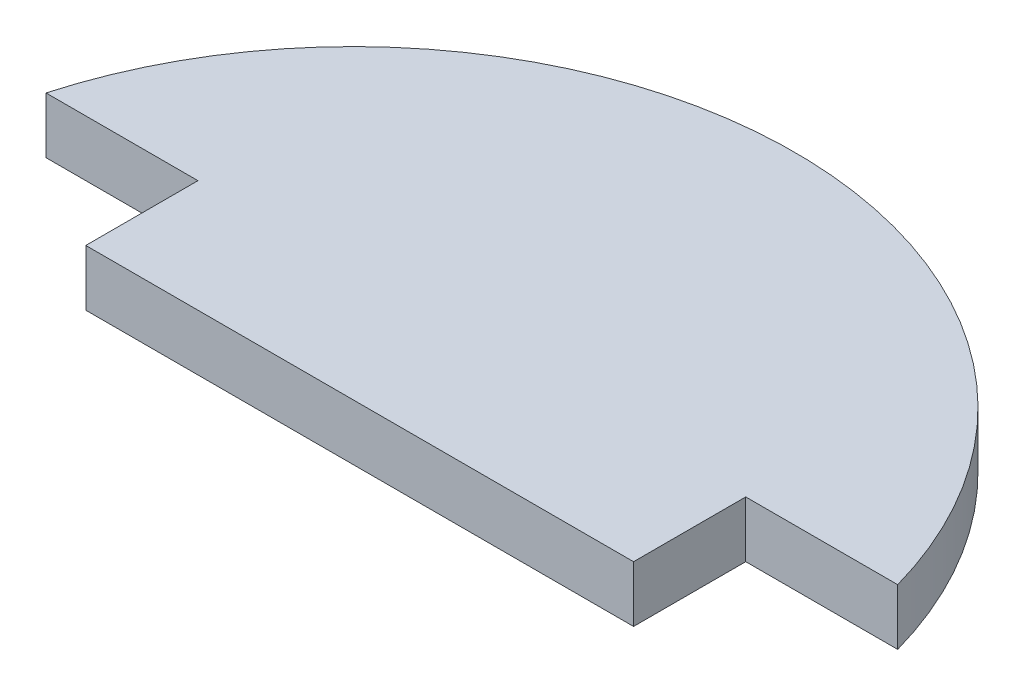
SolidWorks part; units mm, degrees
ref_plane "Front Plane" through (0, 0, 0) normal (0, 0, 1) x (1, 0, 0)
ref_plane "Top Plane" through (0, 0, 0) normal (0, 1, 0) x (1, 0, 0)
ref_plane "Right Plane" through (0, 0, 0) normal (1, 0, 0) x (0, 0, -1)
sketch "Sketch1" plane through (0, 0, 0) normal (0, 1, 0) x (1, 0, 0)
  line L0 (-26.9855, 0) -> (21.8445, 0)
  line L1 (-26.9855, 10) -> (-26.9855, 0)
  line L2 (-26.9855, 0) -> (21.8445, 0)
  line L3 (21.8445, 0) -> (21.8445, 10)
  line L4 (-26.9855, 10) -> (-40.5309, 10)
  line L5 (21.8445, 10) -> (35.3898, 10)
  line L6 (-26.9855, 0) -> (21.8445, 0)
  arc A0 (-40.5309, 10) -> (35.3898, 10) centre (-2.5705, -0.6278) cw
  dimension "D2" = 39.42
  dimension "D5" = 10
  dimension "D6" = 10
extrude "Boss-Extrude1" add sketch "Sketch1" along normal blind 5 contours A0 L4 L1 L0 L3 L5
